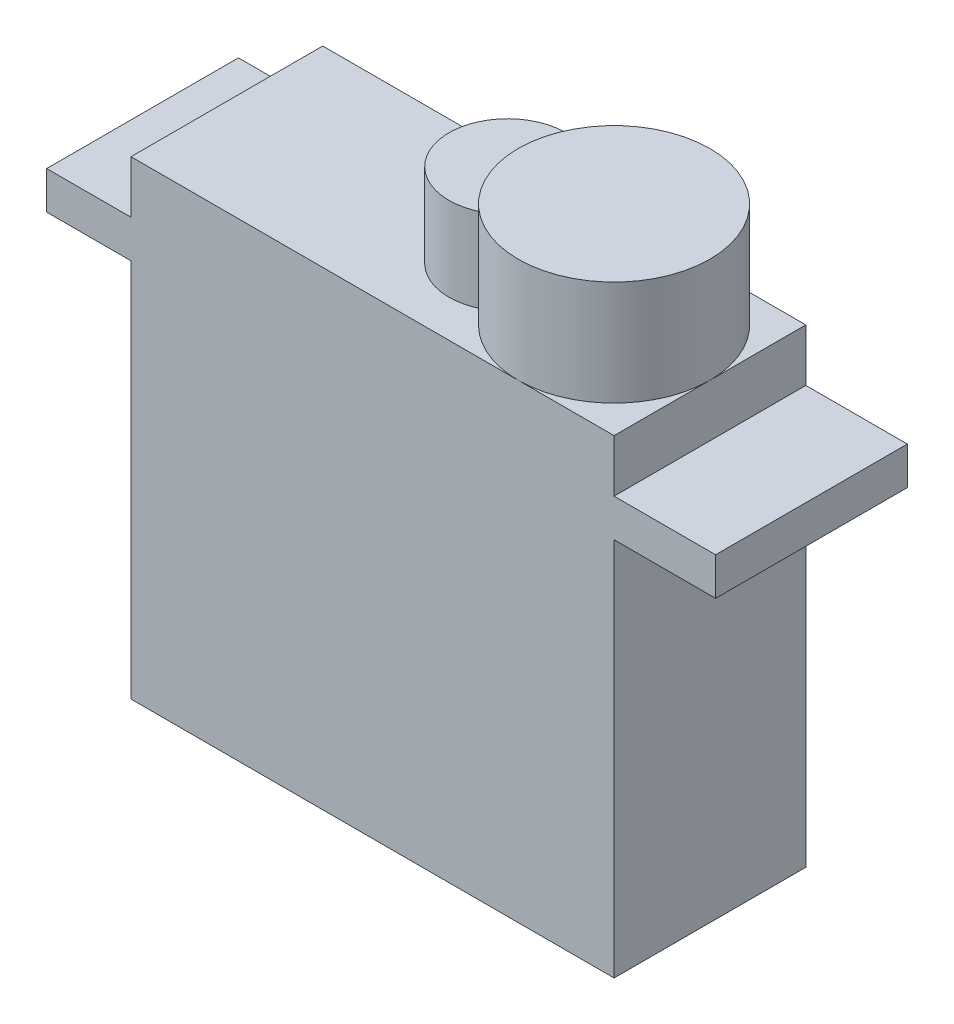
SolidWorks part; units mm, degrees
ref_plane "Front Plane" through (0, 0, 0) normal (0, 0, 1) x (1, 0, 0)
ref_plane "Top Plane" through (0, 0, 0) normal (0, 1, 0) x (1, 0, 0)
ref_plane "Right Plane" through (0, 0, 0) normal (1, 0, 0) x (0, 0, -1)
sketch "Sketch1" plane through (0, 0, 0) normal (0, 1, 0) x (1, 0, 0)
  line L1 (0, 0) -> (23.0378, 0)
  line L2 (0, 0) -> (0, 9.144)
  line L3 (0, 9.144) -> (23.0378, 9.144)
  line L4 (23.0378, 0) -> (23.0378, 9.144)
  dimension "D1" = 23.0378
  dimension "D2" = 9.144
extrude "Boss-Extrude1" add sketch "Sketch1" against normal blind 18.1
sketch "Sketch2" plane through (0, 0, 0) normal (0, 1, 0) x (1, 0, 0)
  line L0 (23.0378, 9.144) -> (0, 9.144) construction
  line L1 (-4.021, 9.144) -> (27.879, 9.144)
  line L2 (-4.021, 9.144) -> (-4.021, 0)
  line L3 (-4.021, 0) -> (27.879, 0)
  line L4 (27.879, 9.144) -> (27.879, 0)
  dimension "D1" = 9.144
  dimension "D2" = 31.9
extrude "Boss-Extrude2" add sketch "Sketch2" along normal blind 1.8
sketch "Sketch3" plane through (0, 1.8, 0) normal (0, 1, 0) x (1, 0, 0)
  line L0 (27.879, 9.144) -> (-4.021, 9.144) construction
  line L1 (0, 0) -> (23.0378, 0)
  line L2 (0, 0) -> (0, 9.144)
  line L3 (0, 9.144) -> (23.0378, 9.144)
  line L4 (23.0378, 0) -> (23.0378, 9.144)
  line L5 (-4.021, 0) -> (27.879, 0) construction
  dimension "D1" = 23.0378
extrude "Boss-Extrude3" add sketch "Sketch3" along normal blind 2.5
sketch "Sketch4" plane through (0, 4.3, 0) normal (0, 1, 0) x (1, 0, 0)
  circle A0 centre (18.4658, 4.572) radius 4.572
  dimension "D1" = 9.144
extrude "Boss-Extrude4" add sketch "Sketch4" along normal blind 5
sketch "Sketch5" plane through (0, 4.3, 0) normal (0, 1, 0) x (1, 0, 0)
  circle A0 centre (13.3858, 4.572) radius 2.794
  circle A1 centre (18.4658, 4.572) radius 4.572 construction
  circle A2 centre (18.4658, 4.572) radius 4.572 construction
  dimension "D2" = 5.588
  dimension "D1" = 5.08
extrude "Boss-Extrude5" add sketch "Sketch5" along normal blind 4
